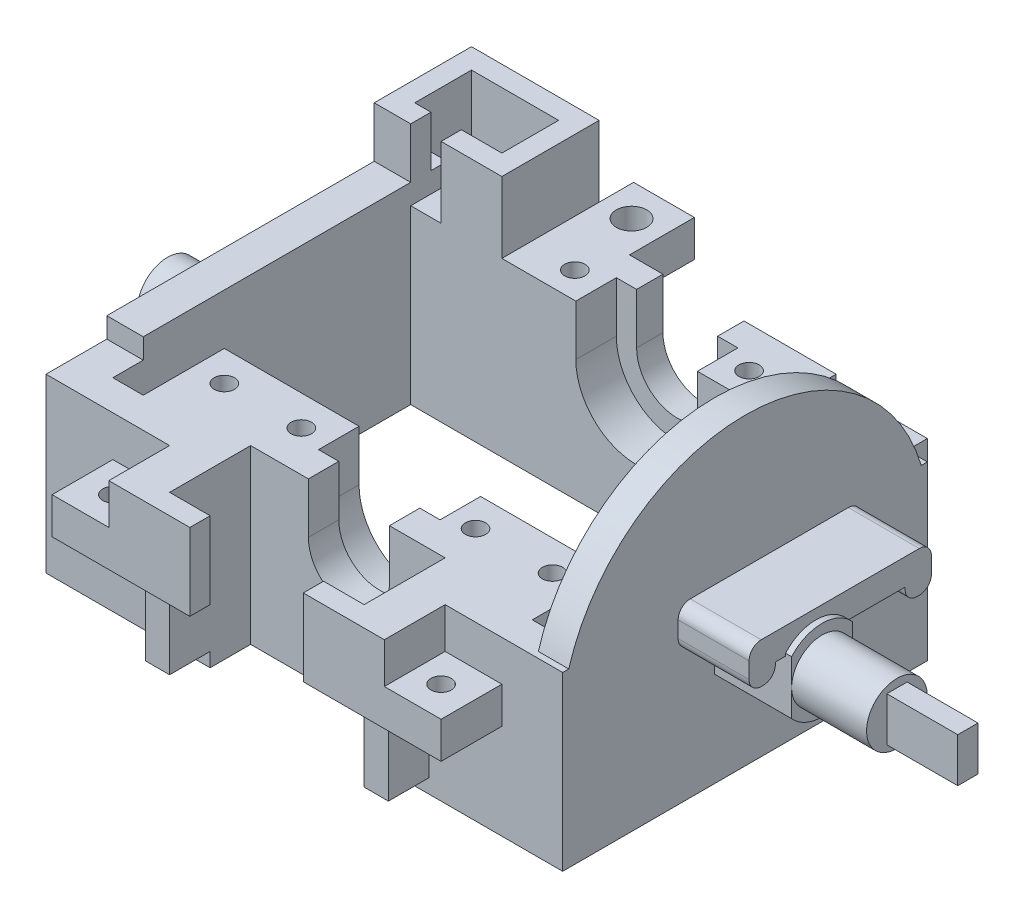
SolidWorks part; units mm, degrees
ref_plane "前视基准面" through (0, 0, 0) normal (0, 0, 1) x (1, 0, 0)
ref_plane "上视基准面" through (0, 0, 0) normal (0, 1, 0) x (1, 0, 0)
ref_plane "右视基准面" through (0, 0, 0) normal (1, 0, 0) x (0, 0, -1)
sketch "草图1" plane through (0, 0, 0) normal (0, 1, 0) x (1, 0, 0)
  line L1 (25.5, 0) -> (25.5, 18)
  line L2 (25.5, 18) -> (0, 18)
  line L3 (0, 18) -> (0, 0)
  line L5 (24, 1.5) -> (19.2, 1.5)
  line L6 (24, 1.5) -> (24, 11.5)
  line L7 (24, 11.5) -> (21, 11.5)
  line L8 (6.6, 1.5) -> (1.8, 1.5)
  line L9 (21, 16.2) -> (21, 11.5)
  line L10 (1.8, 16.2) -> (1.8, 1.5)
  line L11 (21, 16.2) -> (1.8, 16.2)
  line L12 (12.9, 5.5) -> (6.6, 5.5)
  line L13 (6.6, 5.5) -> (6.6, 1.5)
  line L14 (12.9, 5.5) -> (19.2, 5.5)
  line L15 (19.2, 5.5) -> (19.2, 1.5)
  line L18 (8.1, 0) -> (8.1, 2)
  line L19 (8.1, 2) -> (17.7, 2)
  line L20 (17.7, 2) -> (17.7, 0)
  line L21 (17.7, 0) -> (25.5, 0)
  line L22 (8.1, 0) -> (0, 0)
  circle A0 centre (8.6, 4) radius 0.5
  circle A1 centre (17.2, 4) radius 0.5
extrude "凸台-拉伸1" add sketch "草图1" along normal blind 8.5
sketch "草图2" plane through (0, 8.5, 0) normal (0, 1, 0) x (1, 0, 0)
  line L2 (3.3, 5.5) -> (3.3, 1.5)
  line L3 (1.8, 1.5) -> (6.6, 1.5) construction
  line L4 (3.3, 1.5) -> (6.6, 1.5)
  line L5 (6.6, 1.5) -> (6.6, 5.5)
  line L6 (6.6, 5.5) -> (3.3, 5.5)
  line L8 (22.5, 5.5) -> (19.2, 5.5)
  line L9 (19.2, 5.5) -> (19.2, 1.5)
  line L10 (19.2, 1.5) -> (22.5, 1.5)
  line L11 (19.2, 1.5) -> (24, 1.5) construction
  line L12 (22.5, 1.5) -> (22.5, 5.5)
  circle A0 centre (4.8, 4) radius 0.5
  circle A1 centre (21, 4) radius 0.5
extrude "凸台-拉伸2" add sketch "草图2" against normal blind 3
sketch "草图3" plane through (0, 8.5, 0) normal (0, 1, 0) x (1, 0, 0)
  line L0 (17.7, 0) -> (17.7, -2)
  line L1 (17.7, -3) -> (19.7, -3)
  line L2 (19.7, -3) -> (19.7, 0)
  line L3 (17.7, 0) -> (25.5, 0) construction
  line L4 (19.7, 0) -> (17.7, 0)
  line L5 (8.1, 0) -> (6.1, 0)
  line L6 (0, 0) -> (8.1, 0) construction
  line L7 (6.1, 0) -> (6.1, -3)
  line L8 (6.1, -3) -> (8.1, -3)
  line L9 (8.1, -2) -> (8.1, 0)
  line L10 (8.1, -3) -> (10.1, -3)
  line L11 (10.1, -3) -> (10.1, -2)
  line L12 (10.1, -2) -> (8.1, -2)
  line L13 (17.7, -3) -> (15.7, -3)
  line L14 (15.7, -3) -> (15.7, -2)
  line L15 (15.7, -2) -> (17.7, -2)
extrude "凸台-拉伸3" add sketch "草图3" against normal blind 3.8
sketch "草图4" plane through (0, 4.7, 0) normal (0, -1, 0) x (1, 0, 0)
  line L0 (19.7, 3) -> (22.5, 3)
  line L1 (22.5, 3) -> (22.5, 0)
  line L2 (17.7, 0) -> (25.5, 0) construction
  line L3 (22.5, 0) -> (19.7, 0)
  line L4 (19.7, 0) -> (19.7, 3)
  line L5 (6.1, 3) -> (3.3, 3)
  line L6 (3.3, 3) -> (3.3, 0)
  line L7 (0, 0) -> (8.1, 0) construction
  line L8 (3.3, 0) -> (6.1, 0)
  line L9 (6.1, 0) -> (6.1, 3)
  circle A0 centre (4.8, 1.5) radius 0.5
  circle A1 centre (21, 1.5) radius 0.5
extrude "凸台-拉伸4" add sketch "草图4" against normal blind 1.8
sketch "草图5" plane through (0, 4.7, 0) normal (0, -1, 0) x (1, 0, 0)
  line L0 (8.1, 0) -> (8.1, 2)
  line L1 (8.1, 2) -> (6.9, 2)
  line L2 (6.9, 2) -> (6.9, 0)
  line L3 (0, 0) -> (8.1, 0) construction
  line L4 (6.9, 0) -> (8.1, 0)
  line L5 (17.7, 0) -> (17.7, 2)
  line L6 (17.7, 0) -> (17.7, 2) construction
  line L7 (17.7, 2) -> (18.9, 2)
  line L8 (18.9, 2) -> (18.9, 0)
  line L9 (17.7, 0) -> (25.5, 0) construction
  line L10 (18.9, 0) -> (17.7, 0)
extrude "凸台-拉伸5" add sketch "草图5" along normal blind 4
sketch "草图6" plane through (0, 8.5, 0) normal (0, 1, 0) x (1, 0, 0)
  line L1 (0, 18) -> (0, 0) construction
  line L2 (0, 3) -> (1.8, 3)
  line L3 (1.8, 16.2) -> (1.8, 1.5) construction
  line L4 (1.8, 3) -> (1.8, 18)
  line L5 (25.5, 18) -> (0, 18) construction
  line L6 (1.8, 18) -> (0, 18)
  line L7 (0, 18) -> (0, 3)
extrude "凸台-拉伸6" add sketch "草图6" along normal blind 1
sketch "草图7" plane through (0, 8.5, 0) normal (0, 1, 0) x (1, 0, 0)
  line L0 (0, 18) -> (0, 21)
  line L1 (0, 21) -> (6.3, 21)
  line L2 (6.3, 21) -> (6.3, 16.2)
  line L3 (21, 16.2) -> (1.8, 16.2) construction
  line L4 (6.3, 16.2) -> (3.3, 16.2)
  line L5 (3.3, 16.2) -> (3.3, 17.2)
  line L6 (3.3, 17.2) -> (5.3, 17.2)
  line L7 (5.3, 17.2) -> (5.3, 20)
  line L8 (5.3, 20) -> (1, 20)
  line L9 (1, 20) -> (1, 17.2)
  line L10 (1, 17.2) -> (1.8, 17.2)
  line L11 (1.8, 16.2) -> (1.8, 18) construction
  line L12 (1.8, 17.2) -> (1.8, 16.2)
  line L13 (1.8, 16.2) -> (0, 16.2)
  line L14 (0, 18) -> (0, 3) construction
  line L15 (0, 16.2) -> (0, 18)
extrude "凸台-拉伸7" add sketch "草图7" along normal blind 3.5 and the other way blind 4.5
sketch "草图8" plane through (0, 4, 0) normal (0, -1, 0) x (1, 0, 0)
  line L0 (1, -20) -> (5.3, -20)
  line L1 (5.3, -20) -> (5.3, -18)
  line L2 (5.3, -18) -> (1, -18)
  line L3 (1, -18) -> (1, -20)
extrude "凸台-拉伸8" add sketch "草图8" against normal blind 1
sketch "草图9" plane through (0, 0, -18) normal (0, 0, -1) x (-1, 0, 0)
  line L0 (-10.95, 8.5) -> (-10.95, 6)
  line L1 (-25.5, 8.5) -> (-6.3, 8.5) construction
  line L2 (-10.95, 8.5) -> (-6.3, 8.5)
  line L3 (-19.5, 8.5) -> (-14.95, 8.5)
  line L4 (-19.5, 8.5) -> (-19.5, 3.5)
  line L5 (-19.5, 3.5) -> (-16.6917, 3.5)
  line L7 (-14.95, 8.5) -> (-14.95, 6)
  line L10 (-6.3, 8.5) -> (-6.3, 3.5)
  line L11 (-6.3, 3.5) -> (-9.2083, 3.5)
  arc A0 (-14.95, 6) -> (-10.95, 6) centre (-12.95, 6) ccw
  arc A1 (-9.2083, 3.5) -> (-16.6917, 3.5) centre (-12.95, 6) cw
extrude "凸台-拉伸9" add sketch "草图9" along normal blind 1.5
sketch "草图10" plane through (0, 8.5, 0) normal (0, 1, 0) x (1, 0, 0)
  line L0 (6.3, 19.5) -> (6.3, 22.7)
  line L1 (6.3, 22.7) -> (9.3, 22.7)
  line L2 (9.3, 22.7) -> (9.3, 19.5)
  line L3 (6.3, 19.5) -> (10.95, 19.5) construction
  line L4 (9.3, 19.5) -> (6.3, 19.5)
  line L5 (9.3, 22.7) -> (9.3, 21.1)
  circle A0 centre (7.8, 21.1) radius 0.75
  line M40 (10.95, 19.5) -> (6.3, 19.5)
extrude "凸台-拉伸10" add sketch "草图10" against normal blind 1.8 contours L2 L1 L0 A0 M40
sketch "草图12" plane through (0, 0, -18) normal (0, 0, -1) x (-1, 0, 0)
  line L1 (-19.5, 8.5) -> (-19.5, 3.5) construction
  line L2 (-19.5, 6.5) -> (-22.5, 6.5)
  line L3 (-22.5, 6.5) -> (-22.5, 4.7)
  line L4 (-22.5, 4.7) -> (-19.5, 4.7)
  line L5 (-19.5, 4.7) -> (-19.5, 6.5)
extrude "凸台-拉伸11" add sketch "草图12" along normal blind 3
sketch "草图13" plane through (0, 6.5, 0) normal (0, 1, 0) x (1, 0, 0)
  circle A0 centre (21, 19.5) radius 0.75
extrude "切除-拉伸1" cut sketch "草图13" against normal blind 3
sketch "草图14" plane through (0, 8.5, 0) normal (0, 1, 0) x (1, 0, 0)
  circle A0 centre (17.2, 17.5) radius 0.5
  circle A1 centre (8.6, 17.5) radius 0.5
extrude "切除-拉伸2" cut sketch "草图14" against normal blind 3
sketch "草图15" plane through (0, 8.5, 0) normal (0, 1, 0) x (1, 0, 0)
  line L0 (21, 15.7) -> (21, 12.7)
  line L1 (21, 11.5) -> (21, 16.2) construction
  line L2 (21, 12.7) -> (24, 12.7)
  line L3 (24, 12.7) -> (24, 16.7)
  line L4 (24, 16.7) -> (22, 16.7)
  line L5 (22, 16.7) -> (22, 15.7)
  line L6 (22, 15.7) -> (21, 15.7)
extrude "切除-拉伸3" cut sketch "草图15" against normal blind 7
sketch "草图16" plane through (0, 0, -18) normal (0, 0, -1) x (-1, 0, 0)
  line L0 (-14.95, 8.5) -> (-10.95, 8.5)
  line L1 (-10.95, 8.5) -> (-10.95, 6)
  line L2 (-14.95, 6) -> (-14.95, 8.5)
  arc A0 (-10.95, 6) -> (-14.95, 6) centre (-12.95, 6) cw
extrude "切除-拉伸4" cut sketch "草图16" against normal through all
sketch "草图17" plane through (0, 0, -16.2) normal (0, 0, 1) x (1, 0, 0)
  line L1 (15.95, 6) -> (15.95, 8.5)
  line L2 (14.95, 8.5) -> (19.5, 8.5) construction
  line L4 (9.3, 8.5) -> (10.95, 8.5) construction
  line L5 (9.95, 8.5) -> (9.95, 6)
  line L7 (15.95, 8.5) -> (9.95, 8.5)
  arc A0 (15.95, 6) -> (9.95, 6) centre (12.95, 6) cw
extrude "切除-拉伸5" cut sketch "草图17" against normal blind 2 and the other way blind 12.7
sketch "草图18" plane through (0, 8.5, 0) normal (0, 1, 0) x (1, 0, 0)
  line L0 (24, 12.7) -> (24, 11.5)
  line L1 (24, 11.5) -> (22, 11.5)
  line L2 (24, 11.5) -> (21, 11.5) construction
  line L3 (22, 11.5) -> (22, 12.7)
  line L4 (21, 12.7) -> (24, 12.7) construction
  line L5 (22, 12.7) -> (24, 12.7)
extrude "切除-拉伸6" cut sketch "草图18" against normal blind 2.3
sketch "草图19" plane through (25.5, 0, 0) normal (1, 0, 0) x (0, 0, -1)
  line L0 (0, 8.5) -> (18, 8.5) construction
  line L1 (0.3, 8.5) -> (17.7, 8.5)
  arc A1 (0.3, 8.5) -> (17.7, 8.5) centre (9, 5.9254) cw
extrude "凸台-拉伸12" add sketch "草图19" against normal blind 1.5
sketch "草图22" plane through (0, 0, 0) normal (-1, 0, 0) x (0, 0, 1)
  circle A0 centre (-9, 6) radius 1.5
extrude "凸台-拉伸13" add sketch "草图22" along normal blind 3
sketch "草图23" plane through (0, 0, 0) normal (-1, 0, 0) x (0, 0, 1)
  circle A0 centre (-9, 6) radius 2
extrude "凸台-拉伸14" add sketch "草图23" along normal blind 0.5
sketch "草图24" plane through (25.5, 0, 0) normal (1, 0, 0) x (0, 0, -1)
  circle A1 centre (9, 6) radius 1.5
extrude "凸台-拉伸15" add sketch "草图24" along normal blind 7.5
sketch "草图25" plane through (33, 0, 0) normal (1, 0, 0) x (0, 0, -1)
  line L1 (9.5, 6) -> (9.5, 7.0909)
  line L2 (9.5, 7.0909) -> (8.5, 7.0909)
  line L3 (8.5, 7.0909) -> (8.5, 4.9091)
  line L4 (8.5, 4.9091) -> (9.5, 4.9091)
  line L5 (9.5, 4.9091) -> (9.5, 6)
extrude "凸台-拉伸16" add sketch "草图25" along normal blind 3.5
sketch "草图26" plane through (25.5, 0, 0) normal (1, 0, 0) x (0, 0, -1)
  line L1 (9, 8.4984) -> (6.3, 8.4984)
  line L2 (5.7, 7.8984) -> (5.7, 7.0984)
  line L3 (9, 8.4984) -> (14.1, 8.4984)
  line L4 (14.7, 7.8984) -> (14.7, 7.0984)
  line L5 (14.1, 6.4984) -> (14, 6.4984)
  line L6 (13.4, 7.0984) -> (13.4, 7.1984)
  line L7 (13.4, 7.1984) -> (7, 7.1984)
  line L8 (7, 7.1984) -> (7, 7.0984)
  line L9 (6.4, 6.4984) -> (6.3, 6.4984)
  arc A1 (14.1, 8.4984) -> (14.7, 7.8984) centre (14.1, 7.8984) cw
  arc A2 (14.7, 7.0984) -> (14.1, 6.4984) centre (14.1, 7.0984) cw
  arc A3 (14, 6.4984) -> (13.4, 7.0984) centre (14, 7.0984) cw
  arc A4 (7, 7.0984) -> (6.4, 6.4984) centre (6.4, 7.0984) cw
  arc A5 (6.3, 6.4984) -> (5.7, 7.0984) centre (6.3, 7.0984) cw
  arc A6 (5.7, 7.8984) -> (6.3, 8.4984) centre (6.3, 7.8984) cw
  dimension "D1" = 0.6
extrude "凸台-拉伸17" add sketch "草图26" along normal blind 3.5
sketch "草图27" plane through (25.5, 0, 0) normal (1, 0, 0) x (0, 0, -1)
  line L0 (7.5, 6) -> (7.5, 7.3229)
  line L2 (10.5, 7.3229) -> (10.5, 4.6771)
  line L4 (7.5, 4.6771) -> (7.5, 6)
  arc A0 (7.5, 4.6771) -> (10.5, 4.6771) centre (9, 6) ccw
  circle A1 centre (9, 6) radius 1.5 construction
  arc A2 (8.0978, 7.1984) -> (9.9022, 7.1984) centre (9, 6) ccw construction
  arc A3 (10.5, 7.3229) -> (7.5, 7.3229) centre (9, 6) ccw
extrude "凸台-拉伸18" add sketch "草图27" along normal blind 3.8
